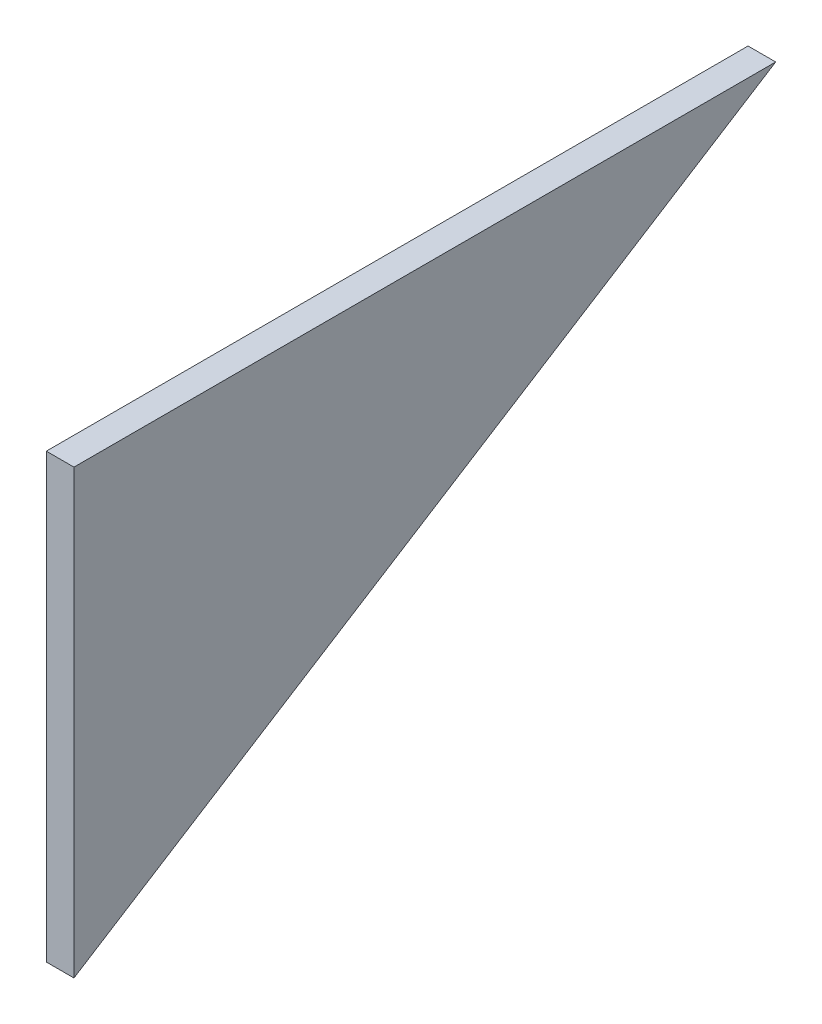
SolidWorks part; units mm, degrees
ref_plane "Front" through (0, 0, 0) normal (0, 0, 1) x (1, 0, 0)
ref_plane "Top" through (0, 0, 0) normal (0, 1, 0) x (1, 0, 0)
ref_plane "Right" through (0, 0, 0) normal (1, 0, 0) x (0, 0, -1)
sketch "Sketch1" plane through (0, 0, 0) normal (1, 0, 0) x (0, 0, -1)
  line L0 (-58.5366, -19.6646) -> (17.5949, 28.3354)
  line L1 (-58.5366, 28.3354) -> (17.5949, 28.3354)
  line L2 (-58.5366, 28.3354) -> (-58.5366, -19.6646)
  dimension "D1" = 48
extrude "Boss-Extrude1" add sketch "Sketch1" along normal blind 3
